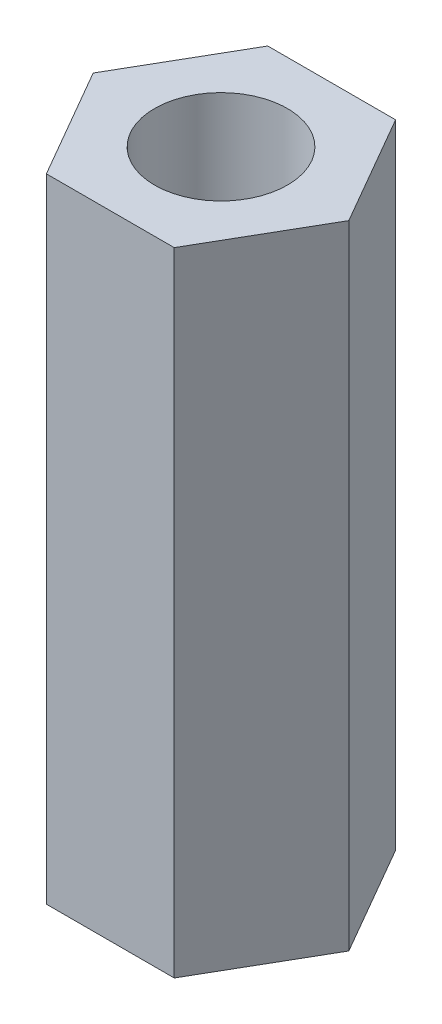
SolidWorks part; units mm, degrees
ref_plane "Front Plane" through (0, 0, 0) normal (0, 0, 1) x (1, 0, 0)
ref_plane "Top Plane" through (0, 0, 0) normal (0, 1, 0) x (1, 0, 0)
ref_plane "Right Plane" through (0, 0, 0) normal (1, 0, 0) x (0, 0, -1)
sketch "Sketch1" plane through (0, 0, 0) normal (0, 1, 0) x (1, 0, 0)
  line L1 (4.0415, 0) -> (2.0207, 3.5)
  line L2 (2.0207, 3.5) -> (-2.0207, 3.5)
  line L3 (-2.0207, 3.5) -> (-4.0415, 0)
  line L4 (-4.0415, 0) -> (-2.0207, -3.5)
  line L5 (-2.0207, -3.5) -> (2.0207, -3.5)
  line L6 (2.0207, -3.5) -> (4.0415, 0)
  circle A0 centre (0, 0) radius 2.1
  circle A2 centre (0, 0) radius 3.5 construction
  dimension "D1" = 4.2
  dimension "D2" = 7
extrude "Boss-Extrude1" add sketch "Sketch1" along normal blind 20
